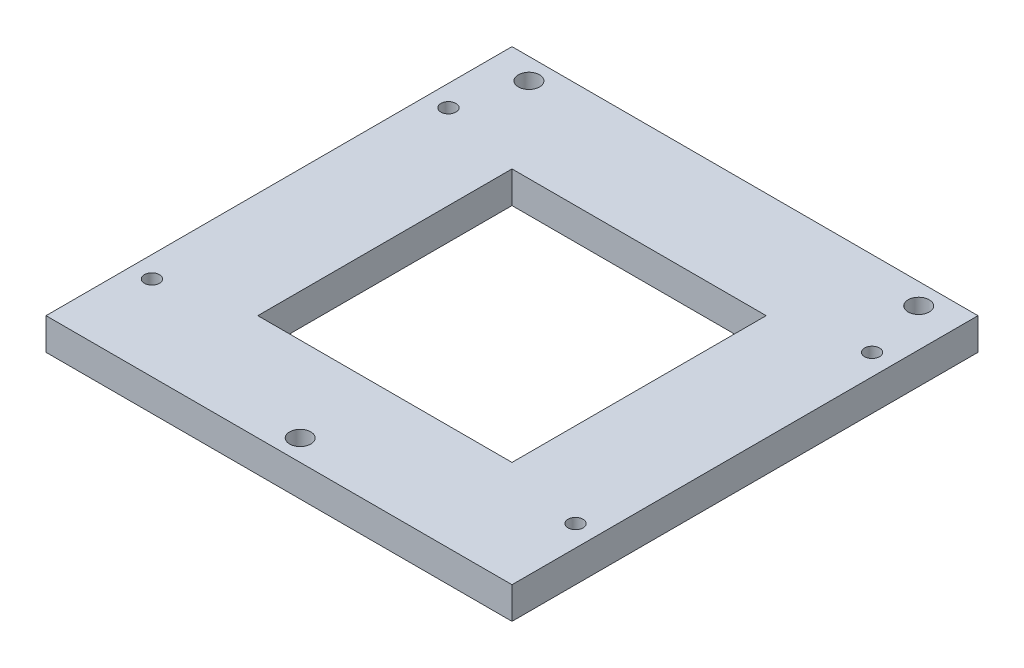
SolidWorks part; units mm, degrees
ref_plane "Front Plane" through (0, 0, 0) normal (0, 0, 1) x (1, 0, 0)
ref_plane "Top Plane" through (0, 0, 0) normal (0, 1, 0) x (1, 0, 0)
ref_plane "Right Plane" through (0, 0, 0) normal (1, 0, 0) x (0, 0, -1)
sketch "Sketch1" plane through (0, 0, 0) normal (0, 1, 0) x (1, 0, 0)
  line L1 (-34.925, 34.925) -> (34.925, 34.925)
  line L2 (-34.925, 34.925) -> (-34.925, -34.925)
  line L3 (-34.925, -34.925) -> (34.925, -34.925)
  line L4 (34.925, 34.925) -> (34.925, -34.925)
  line L5 (-34.925, 34.925) -> (34.925, -34.925) construction
  line L6 (-34.925, -34.925) -> (34.925, 34.925) construction
  point P0 (0, 0)
  dimension "D1" = 69.85
  dimension "D2" = 69.85
extrude "Boss-Extrude1" add sketch "Sketch1" along normal mid plane 4.7625
sketch "Sketch2" plane through (0, 2.3813, 0) normal (0, 1, 0) x (1, 0, 0)
  line L1 (-19.05, 19.05) -> (19.05, 19.05)
  line L2 (-19.05, 19.05) -> (-19.05, -19.05)
  line L3 (-19.05, -19.05) -> (19.05, -19.05)
  line L4 (19.05, 19.05) -> (19.05, -19.05)
  line L5 (-19.05, 19.05) -> (19.05, -19.05) construction
  line L6 (-19.05, -19.05) -> (19.05, 19.05) construction
  point P0 (0, 0)
  dimension "D1" = 38.1
  dimension "D2" = 38.1
extrude "Cut-Extrude1" cut sketch "Sketch2" against normal up to next
hole_wizard "#4-40 Tapped Hole1" positions "Sketch4" profile "Sketch3" tap size "#4-40" standard "ANSI Inch" end condition up to next
sketch "Sketch4" plane through (0, 2.3813, 0) normal (0, 1, 0) x (1, 0, 0)
  point P0 (-31.75, 22.225)
  point P2 (31.75, 22.225)
  dimension "D1" = 31.75
  dimension "D2" = 31.75
  dimension "D3" = 22.225
sketch "Sketch3" plane through (-31.75, 2.3813, -22.225) normal (1, 0, 0) x (0, 0, 1)
  line L0 (0, 0) -> (0, 4.7635)
  line L1 (0, 4.7635) -> (1.1303, 4.7635)
  line L2 (1.1303, 4.7635) -> (1.1303, 0)
  line L5 (1.1303, 0) -> (0, 0)
  line L11 (0, -6.35) -> (0, 107.95) construction
  dimension "Thru Tap Drill Dia." = 2.2606
  dimension "Thru Tap Drill Depth" = 4.7635
cosmetic thread "Hole Thread1" parameters "D2"=2.8448
cosmetic thread "Hole Thread2" parameters "D2"=2.8448
hole_wizard "1/8 (0.125) Diameter Hole1" positions "Sketch6" profile "Sketch5" hole size "1/8" standard "ANSI Inch" end condition up to next
sketch "Sketch6" plane through (0, 2.3813, 0) normal (0, 1, 0) x (1, 0, 0)
  point P0 (-29.21, 31.75)
  point P2 (29.21, 31.75)
  point P4 (0, -31.75)
  dimension "D1" = 29.21
  dimension "D2" = 29.21
  dimension "D3" = 31.75
  dimension "D4" = 31.75
sketch "Sketch5" plane through (-29.21, 2.3813, -31.75) normal (1, 0, 0) x (0, 0, 1)
  line L0 (0, 0) -> (0, 4.7625)
  line L1 (0, 4.7625) -> (1.5875, 4.7625)
  line L2 (1.5875, 4.7625) -> (1.5875, 0)
  line L5 (1.5875, 0) -> (0, 0)
  line L11 (0, -6.35) -> (0, 107.95) construction
  dimension "Thru Hole Dia." = 3.175
  dimension "Thru Hole Depth" = 4.7625
mirror "Mirror1" about plane through (0, 0, 0) normal (0, 0, 1) of "#4-40 Tapped Hole1"
